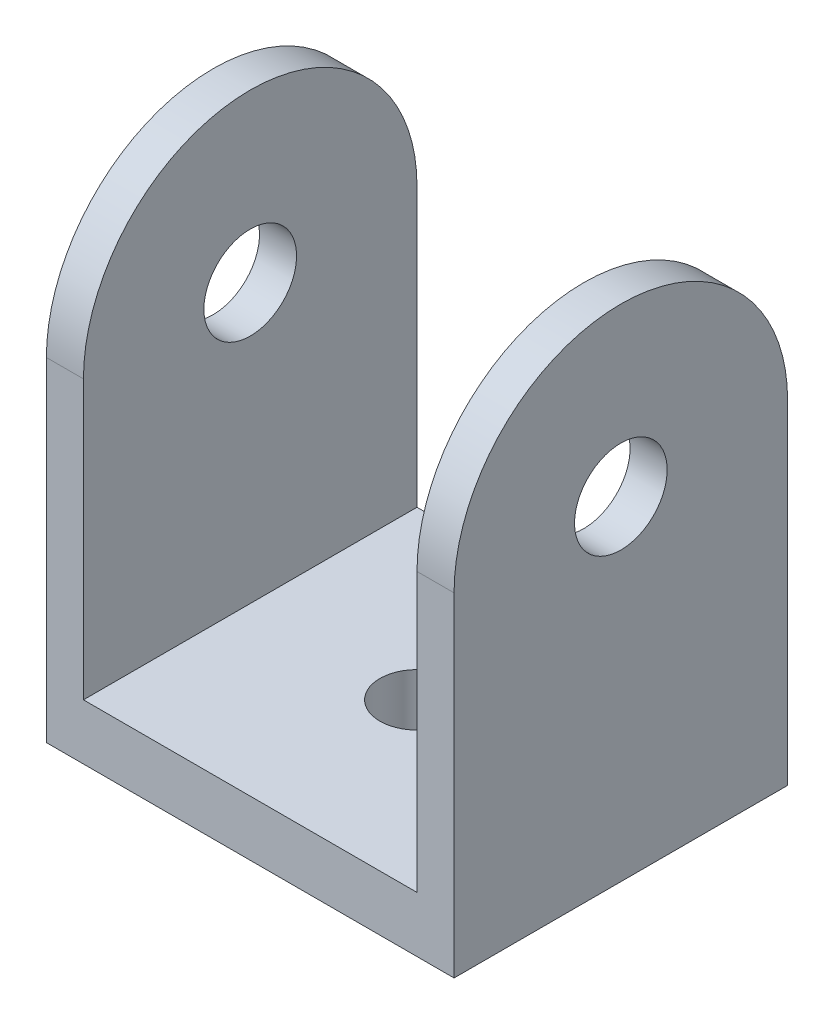
SolidWorks part; units mm, degrees
ref_plane "Front Plane" through (0, 0, 0) normal (0, 0, 1) x (1, 0, 0)
ref_plane "Top Plane" through (0, 0, 0) normal (0, 1, 0) x (1, 0, 0)
ref_plane "Right Plane" through (0, 0, 0) normal (1, 0, 0) x (0, 0, -1)
sketch "Sketch1" plane through (0, 0, 0) normal (0, 1, 0) x (1, 0, 0)
  line L1 (-11, 9) -> (11, 9)
  line L2 (-11, 9) -> (-11, -9)
  line L3 (-11, -9) -> (11, -9)
  line L4 (11, 9) -> (11, -9)
  line L5 (-11, 9) -> (11, -9) construction
  line L6 (-11, -9) -> (11, 9) construction
  circle A0 centre (0, 0) radius 2
  point P0 (0, 0)
  dimension "D3" = 4
  dimension "D1" = 22
  dimension "D2" = 18
extrude "Boss-Extrude2" add sketch "Sketch1" along normal blind 3
sketch "Sketch2" plane through (0, 3, 0) normal (0, 1, 0) x (1, 0, 0)
  line L0 (-11, -9) -> (11, -9) construction
  line L1 (-11, 9) -> (-9, 9)
  line L2 (-11, 9) -> (-11, -9)
  line L3 (-11, -9) -> (-9, -9)
  line L4 (-9, 9) -> (-9, -9)
  dimension "D1" = 2
extrude "Boss-Extrude3" add sketch "Sketch2" along normal blind 24
sketch "Sketch3" plane through (-11, 0, 0) normal (-1, 0, 0) x (0, 0, 1)
  line L0 (-9, 18) -> (9, 18) construction
  line L1 (-9, 27) -> (-9, 0) construction
  line L2 (9, 27) -> (9, 0) construction
  line L3 (-9, 27) -> (9, 27) construction
  line L4 (0, 0) -> (0, 27) construction
  line L5 (-9, 0) -> (9, 0) construction
  arc A0 (-9, 18) -> (9, 18) centre (0, 18) cw
  circle A1 centre (0, 18) radius 2.5
  line M3 (9, 0) -> (9, 27)
  line M4 (9, 27) -> (-9, 27)
  line M5 (-9, 27) -> (-9, 0)
  dimension "D2" = 5
  dimension "D1" = 9
extrude "Cut-Extrude1" cut sketch "Sketch3" against normal blind 24 contours A0 M4 M3 | A0 M5 M4 | A1
ref_plane "Plane1" through (0, 0, 0) normal (1, 0, 0) x (0, 0, -1)
mirror "Mirror1" about plane through (0, 0, 0) normal (1, 0, 0) of "Boss-Extrude2", "Cut-Extrude1", "Boss-Extrude3"
